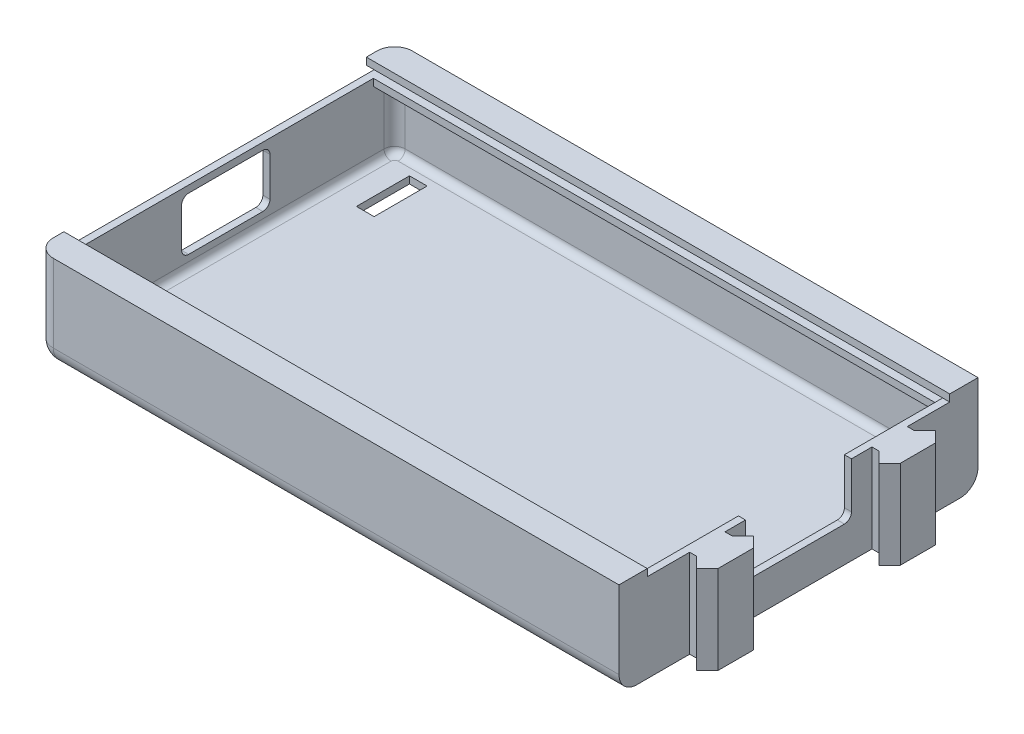
SolidWorks part; units mm, degrees
ref_plane "Front Plane" through (0, 0, 0) normal (0, 0, 1) x (1, 0, 0)
ref_plane "Top Plane" through (0, 0, 0) normal (0, 1, 0) x (1, 0, 0)
ref_plane "Right Plane" through (0, 0, 0) normal (1, 0, 0) x (0, 0, -1)
sketch "Sketch1" plane through (0, 0, 0) normal (0, 1, 0) x (1, 0, 0)
  line L1 (82.55, -50.8) -> (-82.55, -50.8)
  line L2 (82.55, -50.8) -> (82.55, 50.8)
  line L3 (82.55, 50.8) -> (-82.55, 50.8)
  line L4 (-82.55, -50.8) -> (-82.55, 50.8)
  line L5 (82.55, -50.8) -> (-82.55, 50.8) construction
  line L6 (82.55, 50.8) -> (-82.55, -50.8) construction
  point P0 (0, 0)
  dimension "D1" = 101.6
  dimension "6in" = 165.1
extrude "Boss-Extrude1" add sketch "Sketch1" along normal blind 25
shell "Shell1" thickness 2
sketch "Sketch2" plane through (0, 2, 0) normal (0, 1, 0) x (1, 0, 0)
  line L0 (82.55, -50.8) -> (82.55, 50.8) construction
  line L1 (-67.35, 29.8) -> (-72.35, 29.8)
  line L2 (-67.35, 29.8) -> (-67.35, 44.8)
  line L3 (-67.35, 44.8) -> (-72.35, 44.8)
  line L4 (-72.35, 29.8) -> (-72.35, 44.8)
  line L5 (-67.35, 29.8) -> (-72.35, 44.8) construction
  line L6 (-67.35, 44.8) -> (-72.35, 29.8) construction
  line L7 (82.55, 50.8) -> (-82.55, 50.8) construction
  point P0 (-69.85, 37.3)
  dimension "D1" = 5
  dimension "D2" = 15
  dimension "D3" = 152.4
  dimension "D4" = 6
extrude "Cut-Extrude1" cut sketch "Sketch2" against normal blind 25
sketch "Sketch3" plane through (82.55, 0, 0) normal (1, 0, 0) x (0, 0, -1)
  line L0 (-50.8, 25) -> (50.8, 25) construction
  line L1 (-15, 40) -> (15, 40)
  line L2 (-15, 40) -> (-15, 12)
  line L3 (-13, 10) -> (13, 10)
  line L4 (15, 40) -> (15, 12)
  line L5 (-15, 40) -> (15, 10) construction
  line L6 (-15, 10) -> (15, 40) construction
  arc A0 (-15, 12) -> (-13, 10) centre (-13, 12) ccw
  arc A1 (13, 10) -> (15, 12) centre (13, 12) ccw
  point P0 (0, 25)
  dimension "D3" = 2
  dimension "D1" = 30
  dimension "D2" = 15
extrude "Cut-Extrude2" cut sketch "Sketch3" against normal up to next
fillet "Fillet1" radius 5 2 edges at (-82.55, 12.5, 50.8) (-82.55, 12.5, -50.8)
fillet "Fillet2" radius 3 4 edges at (80.55, 13.5, -48.8) (80.55, 13.5, 48.8) (-80.55, 13.5, 48.8) (-80.55, 13.5, -48.8)
fillet "Fillet3" radius 2 8 edges at (79.6713, 2, 47.9213) (0, 2, 48.8) (-79.6713, 2, 47.9213) (-80.55, 2, 0) (-79.6713, 2, -47.9213) (0, 2, -48.8) (79.6713, 2, -47.9213) (80.55, 2, 0)
fillet "Fillet4" radius 5 5 edges at (2.5, 0, 50.8) (-81.0855, 0, 49.3355) (-82.55, 0, 0) (-81.0855, 0, -49.3355) (2.5, 0, -50.8)
sketch "Sketch4" plane through (-82.55, 0, 0) normal (-1, 0, 0) x (0, 0, 1)
  line L0 (-45.8, 25) -> (45.8, 25) construction
  line L1 (45.8, 27.2) -> (-45.8, 27.2)
  line L2 (45.8, 27.2) -> (45.8, 22.8)
  line L3 (45.8, 22.8) -> (-45.8, 22.8)
  line L4 (-45.8, 27.2) -> (-45.8, 22.8)
  line L5 (45.8, 27.2) -> (-45.8, 22.8) construction
  line L6 (45.8, 22.8) -> (-45.8, 27.2) construction
  line L7 (-45.8, 25) -> (-45.8, 5) construction
  point P0 (0, 25)
  dimension "D1" = 2.2
extrude "Cut-Extrude3" cut sketch "Sketch4" against normal up to next
sketch "Sketch8" plane through (0, 25, 0) normal (0, 1, 0) x (1, 0, 0)
  line L0 (-77.55, -48.8) -> (77.55, -48.8) construction
  line L1 (77.55, 48.8) -> (-77.55, 48.8) construction
  line L2 (-77.55, -48.8) -> (77.55, -48.8)
  line L3 (77.55, 48.8) -> (-77.55, 48.8)
  line L4 (-80.55, 45.8) -> (80.55, 45.8)
  line L5 (-80.55, -45.8) -> (80.55, -45.8)
  arc A0 (80.55, 45.8) -> (77.55, 48.8) centre (77.55, 45.8) ccw construction
  arc A1 (77.55, -48.8) -> (80.55, -45.8) centre (77.55, -45.8) ccw construction
  arc A2 (-80.55, -45.8) -> (-77.55, -48.8) centre (-77.55, -45.8) ccw construction
  arc A3 (-77.55, 48.8) -> (-80.55, 45.8) centre (-77.55, 45.8) ccw construction
  arc A4 (80.55, 45.8) -> (77.55, 48.8) centre (77.55, 45.8) ccw
  arc A5 (77.55, -48.8) -> (80.55, -45.8) centre (77.55, -45.8) ccw
  arc A6 (-80.55, -45.8) -> (-77.55, -48.8) centre (-77.55, -45.8) ccw
  arc A7 (-77.55, 48.8) -> (-80.55, 45.8) centre (-77.55, 45.8) ccw
extrude "Boss-Extrude4" add sketch "Sketch8" against normal blind 2.2
sketch "Sketch5" plane through (0, 25, 0) normal (0, 1, 0) x (1, 0, 0)
  line L0 (-77.55, -50.8) -> (82.55, -50.8) construction
  line L1 (82.55, 50.8) -> (-77.55, 50.8) construction
  line L2 (-77.55, -50.8) -> (82.55, -50.8)
  line L3 (82.55, 50.8) -> (-77.55, 50.8)
  line L4 (-82.55, -45.8) -> (-82.55, -42.8)
  line L5 (-82.55, 45.8) -> (-82.55, -45.8) construction
  line L6 (-82.55, -42.8) -> (82.55, -42.8)
  line L7 (82.55, -50.8) -> (82.55, -15) construction
  line L8 (82.55, -42.8) -> (82.55, -50.8)
  line L9 (-82.55, 45.8) -> (-82.55, 42.8)
  line L10 (-82.55, 42.8) -> (82.55, 42.8)
  line L11 (82.55, 15) -> (82.55, 50.8) construction
  line L12 (82.55, 42.8) -> (82.55, 50.8)
  arc A0 (-82.55, -45.8) -> (-77.55, -50.8) centre (-77.55, -45.8) ccw construction
  arc A1 (-77.55, 50.8) -> (-82.55, 45.8) centre (-77.55, 45.8) ccw construction
  arc A2 (-82.55, -45.8) -> (-77.55, -50.8) centre (-77.55, -45.8) ccw
  arc A3 (-77.55, 50.8) -> (-82.55, 45.8) centre (-77.55, 45.8) ccw
  dimension "D1" = 8
extrude "Boss-Extrude2" add sketch "Sketch5" along normal blind 2
pattern_linear "LPattern1" count 2 spacing 4.2 along (0, -1, 0) of "Boss-Extrude2"
sketch "Sketch6" plane through (0, 0, 0) normal (0, -1, 0) x (1, 0, 0)
  line L0 (82.55, -30.8) -> (84.55, -30.8)
  line L1 (82.55, 45.8) -> (82.55, -45.8) construction
  line L2 (84.55, -30.8) -> (87.55, -33.8)
  line L3 (87.55, -33.8) -> (90.55, -30.8)
  line L4 (90.55, -30.8) -> (90.55, -20.8)
  line L5 (90.55, -20.8) -> (87.55, -17.8)
  line L6 (87.55, -17.8) -> (84.55, -20.8)
  line L7 (84.55, -20.8) -> (82.55, -20.8)
  line L8 (82.55, -20.8) -> (82.55, -30.8)
  line L9 (82.55, -50.8) -> (-77.55, -50.8) construction
  line L10 (0, 0) -> (82.55, 0) construction
  line L11 (82.55, 20.8) -> (82.55, 30.8)
  line L12 (84.55, 20.8) -> (82.55, 20.8)
  line L13 (87.55, 17.8) -> (84.55, 20.8)
  line L14 (90.55, 20.8) -> (87.55, 17.8)
  line L15 (90.55, 30.8) -> (90.55, 20.8)
  line L16 (87.55, 33.8) -> (90.55, 30.8)
  line L17 (84.55, 30.8) -> (87.55, 33.8)
  line L18 (82.55, 30.8) -> (84.55, 30.8)
  point P17 (82.55, -25.8)
  dimension "D1" = 6
  dimension "D2" = 8
  dimension "D3" = 25
  dimension "D4" = 10
extrude "Boss-Extrude3" add sketch "Sketch6" against normal up to surface (25 mm away) up to face at (81.55, 25, -28.9)
sketch "Sketch7" plane through (-80.55, 0, 0) normal (1, 0, 0) x (0, 0, -1)
  line L0 (42.8, 22.8) -> (-42.8, 22.8) construction
  line L1 (11.52, 20.8) -> (-9.48, 20.8)
  line L2 (13.52, 18.8) -> (13.52, 7.8)
  line L3 (11.52, 5.8) -> (-9.48, 5.8)
  line L4 (-11.48, 18.8) -> (-11.48, 7.8)
  line L5 (13.52, 20.8) -> (-11.48, 5.8) construction
  line L6 (13.52, 5.8) -> (-11.48, 20.8) construction
  arc A0 (-9.48, 20.8) -> (-11.48, 18.8) centre (-9.48, 18.8) ccw
  arc A1 (-9.48, 5.8) -> (-11.48, 7.8) centre (-9.48, 7.8) cw
  arc A2 (13.52, 7.8) -> (11.52, 5.8) centre (11.52, 7.8) cw
  arc A3 (11.52, 20.8) -> (13.52, 18.8) centre (11.52, 18.8) cw
  point P0 (1.02, 13.3)
  dimension "D1" = 2
  dimension "D2" = 25
  dimension "D3" = 15
  dimension "D4" = 2
extrude "Cut-Extrude4" cut sketch "Sketch7" against normal up to next
